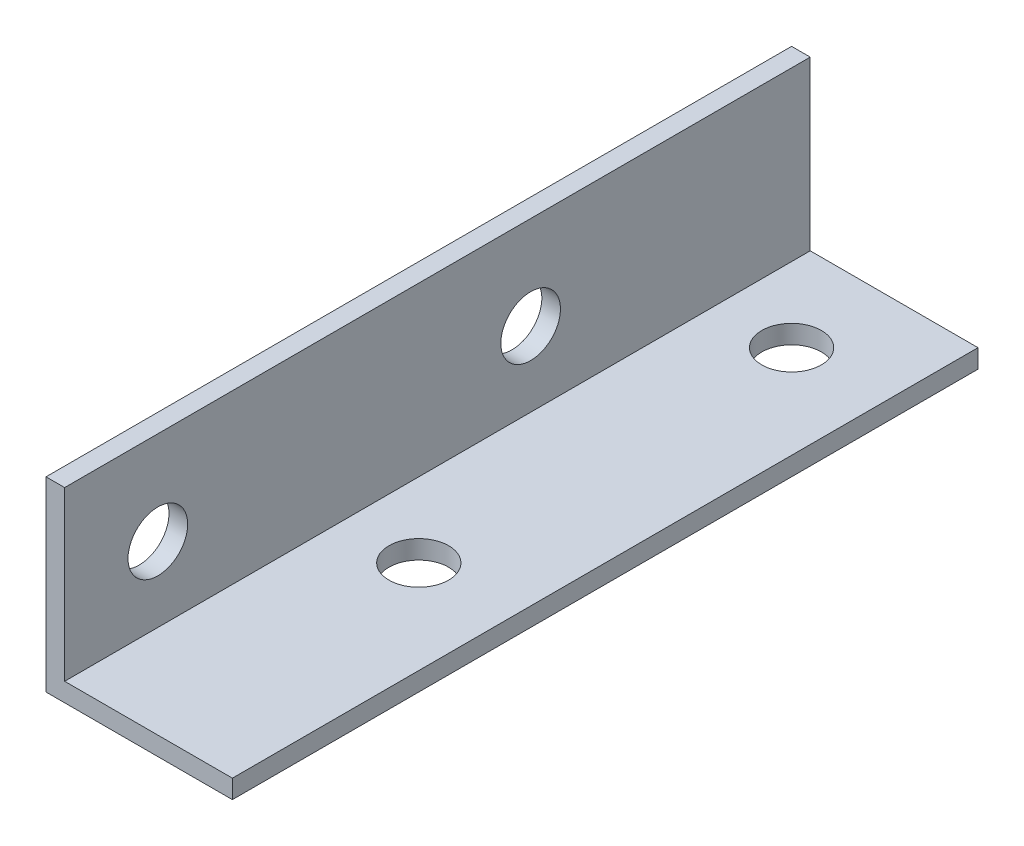
SolidWorks part; units mm, degrees
ref_plane "正面" through (0, 0, 0) normal (0, 0, 1) x (1, 0, 0)
ref_plane "平面" through (0, 0, 0) normal (0, 1, 0) x (1, 0, 0)
ref_plane "右側面" through (0, 0, 0) normal (1, 0, 0) x (0, 0, -1)
sketch "ｽｹｯﾁ1" plane through (0, 0, 0) normal (0, 0, 1) x (1, 0, 0)
  line L0 (-4, 5) -> (-4, -4)
  line L1 (5, -5) -> (-5, -5)
  line L2 (5, -5) -> (5, -4)
  line L3 (-4, 5) -> (-5, 5)
  line L4 (-5, -5) -> (-5, 5)
  line L5 (5, -5) -> (-5, 5) construction
  line L6 (5, 5) -> (-5, -5) construction
  line L7 (-4, -4) -> (5, -4)
  point P0 (0, 0)
  dimension "D1" = 10
  dimension "D2" = 1
  dimension "D3" = 10
  dimension "D4" = 1
extrude "ﾎﾞｽ - 押し出し1" add sketch "ｽｹｯﾁ1" along normal blind 40
sketch "ｽｹｯﾁ2" plane through (0, -5, 0) normal (0, -1, 0) x (1, 0, 0)
  line L0 (0, 0) -> (0, 40) construction
  line L1 (-5, 0) -> (5, 0) construction
  line L2 (-5, 40) -> (5, 40) construction
  circle A1 centre (0, 5) radius 1.6
  circle A2 centre (0, 25) radius 1.6
  dimension "D1" = 20
  dimension "D2" = 5
  dimension "D3" = 3.2
extrude "ｶｯﾄ - 押し出し1" cut sketch "ｽｹｯﾁ2" against normal through all and the other way through all
sketch "ｽｹｯﾁ3" plane through (-5, 0, 0) normal (-1, 0, 0) x (0, 0, 1)
  line L0 (40, 0) -> (0, 0) construction
  line L1 (40, 5) -> (40, -5) construction
  line L2 (0, 5) -> (0, -5) construction
  circle A0 centre (15, 0) radius 1.6
  circle A1 centre (35, 0) radius 1.6
  dimension "D1" = 20
  dimension "D2" = 5
  dimension "D3" = 3.2
extrude "ｶｯﾄ - 押し出し2" cut sketch "ｽｹｯﾁ3" against normal through all
